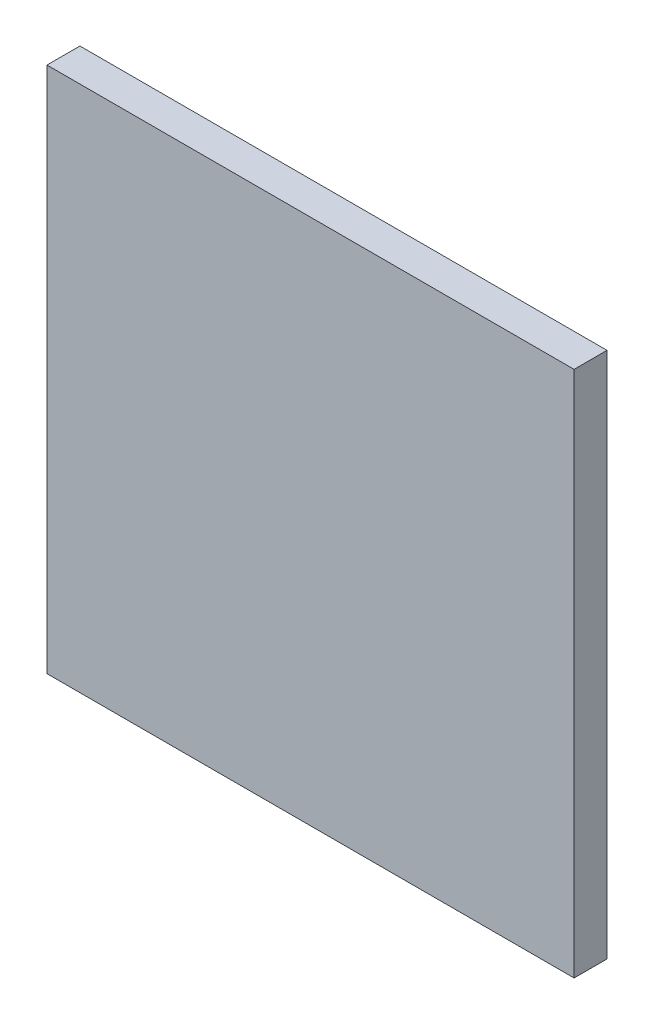
SolidWorks part; units mm, degrees
material "Thornel VCB-20 Carbon Cloth"
ref_plane "Front Plane" through (0, 0, 0) normal (0, 0, 1) x (1, 0, 0)
ref_plane "Top Plane" through (0, 0, 0) normal (0, 1, 0) x (1, 0, 0)
ref_plane "Right Plane" through (0, 0, 0) normal (1, 0, 0) x (0, 0, -1)
sketch "Sketch1" plane through (0, 0, 0) normal (0, 0, 1) x (1, 0, 0)
  line L1 (-152.4, -152.4) -> (152.4, -152.4)
  line L2 (-152.4, -152.4) -> (-152.4, 152.4)
  line L3 (-152.4, 152.4) -> (152.4, 152.4)
  line L4 (152.4, -152.4) -> (152.4, 152.4)
  line L5 (-152.4, -152.4) -> (152.4, 152.4) construction
  line L6 (-152.4, 152.4) -> (152.4, -152.4) construction
  point P0 (0, 0)
  dimension "D1" = 304.8
  dimension "D2" = 304.8
extrude "Boss-Extrude1" add sketch "Sketch1" along normal blind 19.05
sketch "Sketch2" plane through (0, 0, 0) normal (0, 0, -1) x (-1, 0, 0)
  line L0 (152.4, 152.4) -> (152.4, -152.4) construction
  line L1 (-127, 127) -> (127, 127)
  line L2 (-127, 127) -> (-127, -127)
  line L3 (-127, -127) -> (127, -127)
  line L4 (127, 127) -> (127, -127)
  line L5 (-127, 127) -> (127, -127) construction
  line L6 (-127, -127) -> (127, 127) construction
  line L7 (152.4, -152.4) -> (-152.4, -152.4) construction
  point P0 (0, 0)
  dimension "D1" = 25.4
  dimension "D2" = 25.4
extrude "Cut-Extrude1" cut sketch "Sketch2" against normal blind 18.796
sketch "Sketch3" plane through (0, 0, 18.796) normal (0, 0, -1) x (-1, 0, 0)
  line L0 (152.4, 152.4) -> (152.4, -152.4) construction
  line L1 (-139.7, 139.7) -> (139.7, 139.7)
  line L2 (-139.7, 139.7) -> (-139.7, -139.7)
  line L3 (-139.7, -139.7) -> (139.7, -139.7)
  line L4 (139.7, 139.7) -> (139.7, -139.7)
  line L5 (-139.7, 139.7) -> (139.7, -139.7) construction
  line L6 (-139.7, -139.7) -> (139.7, 139.7) construction
  line L7 (152.4, -152.4) -> (-152.4, -152.4) construction
  point P0 (0, 0)
  dimension "D1" = 12.7
  dimension "D2" = 12.7
extrude "Cut-Extrude2" cut sketch "Sketch3" along normal blind 11.684
